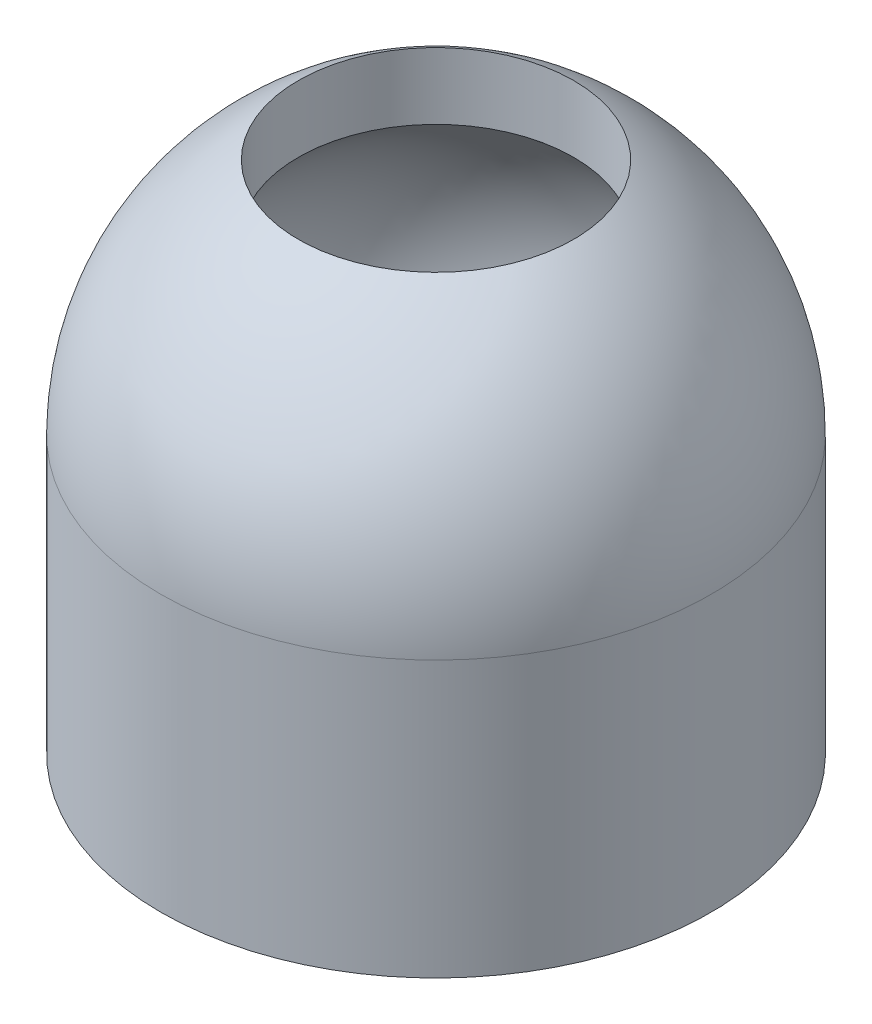
SolidWorks part; units mm, degrees
ref_plane "Front Plane" through (0, 0, 0) normal (0, 0, 1) x (1, 0, 0)
ref_plane "Top Plane" through (0, 0, 0) normal (0, 1, 0) x (1, 0, 0)
ref_plane "Right Plane" through (0, 0, 0) normal (1, 0, 0) x (0, 0, -1)
sketch "Sketch1" plane through (0, 0, 0) normal (0, 0, 1) x (1, 0, 0)
  line L0 (0, 5) -> (0, -5)
  line L2 (5, 0) -> (5, -5)
  line L3 (5, -5) -> (0, -5)
  arc A0 (0, -5) -> (0, 5) centre (0, 0) ccw
  point P1 (0, 0)
revolve "Revolve2" add sketch "Sketch1" angle 360 about L0
sketch "Sketch2" plane through (0, 0, 0) normal (0, 0, 1) x (1, 0, 0)
  line L0 (0, 4) -> (0, -4)
  arc A0 (0, -4) -> (0, 4) centre (0, 0) ccw
revolve "Cut-Revolve1" cut sketch "Sketch2" angle 360 about L0
ref_plane "Plane1" through (0, 5, 0) normal (0, 1, 0) x (1, 0, 0)
sketch "Sketch3" plane through (0, 5, 0) normal (0, 1, 0) x (1, 0, 0)
  circle A0 centre (0, 0) radius 2.5
extrude "Cut-Extrude1" cut sketch "Sketch3" against normal blind 3 contours A0
